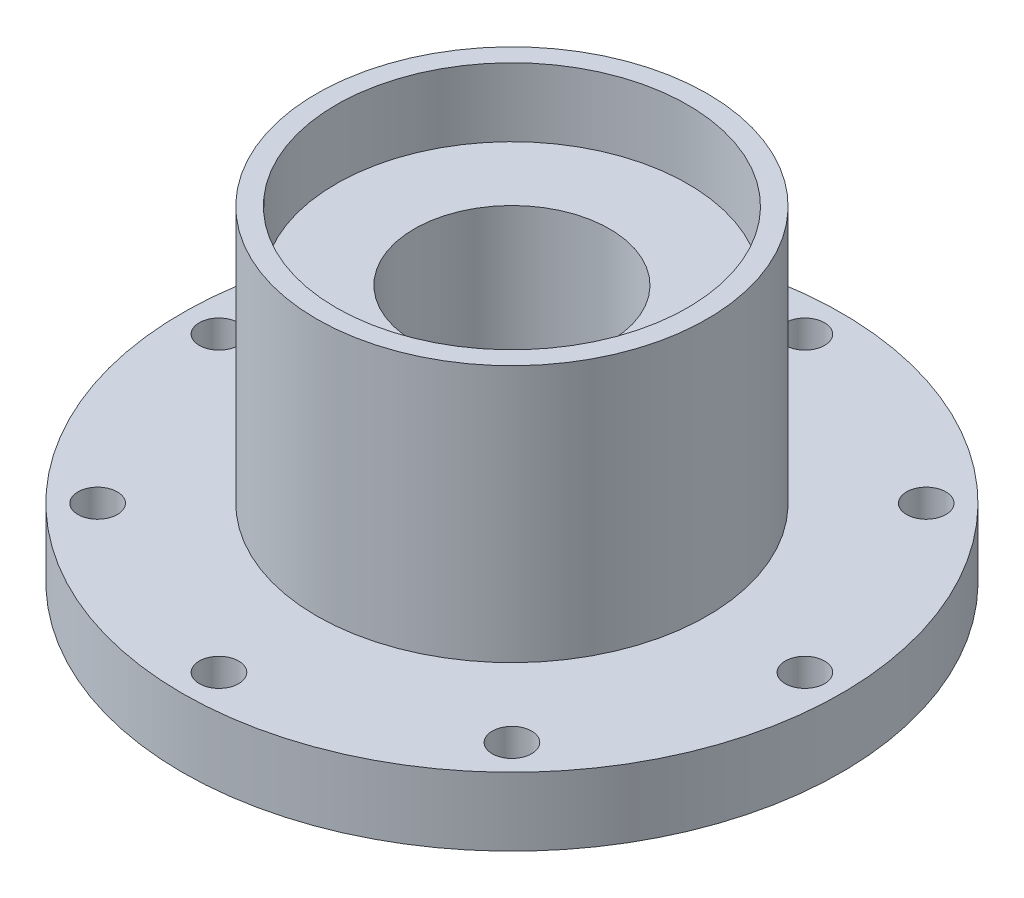
SolidWorks part; units mm, degrees
ref_plane "Front Plane" through (0, 0, 0) normal (0, 0, 1) x (1, 0, 0)
ref_plane "Top Plane" through (0, 0, 0) normal (0, 1, 0) x (1, 0, 0)
ref_plane "Right Plane" through (0, 0, 0) normal (1, 0, 0) x (0, 0, -1)
sketch "Sketch1" plane through (0, 0, 0) normal (1, 0, 0) x (0, 0, -1)
  line L0 (0, 150) -> (0, -163.75) construction
  line L1 (-60, -15.2609) -> (-60, -94.2609)
  line L2 (-60, -94.2609) -> (-101.25, -94.2609)
  line L3 (-101.25, -94.2609) -> (-101.25, -107.2609)
  line L4 (-101.25, -115.2609) -> (-54, -115.2609)
  line L5 (-54, -115.2609) -> (-54, -94.2609)
  line L6 (-54, -94.2609) -> (-34.1, -94.2609)
  line L7 (-30, -94.1609) -> (-30, -36.2609)
  line L8 (-54, -15.2609) -> (-60, -15.2609)
  line L9 (-34.1, -94.2609) -> (-30, -94.1609)
  line L10 (-54, -15.2609) -> (-54, -36.2609)
  line L11 (-54, -36.2609) -> (-30, -36.2609)
  line L12 (-30, -15.2609) -> (-54, -15.2609) construction
  line L13 (-30, -36.2609) -> (-30, -15.2609) construction
  line L17 (-101.25, -107.2609) -> (-101.25, -115.2609) construction
  line L18 (-101.25, -115.2609) -> (-101.25, -107.2609)
  point P10 (-30, -94.2609)
  dimension "D1" = 108
  dimension "D2" = 21
  dimension "D3" = 79
  dimension "D4" = 202.5
  dimension "D5" = 30
  dimension "D6" = 60
  dimension "D7" = 21
  dimension "D8" = 21
revolve "Revolve1" add sketch "Sketch1" angle 360 about L0
sketch "Sketch2" plane through (0, -94.2609, 0) normal (0, 1, 0) x (1, 0, 0)
  circle A0 centre (0, 90) radius 6.05
  circle A1 centre (63.6396, 63.6396) radius 6.05
  circle A2 centre (90, 0) radius 6.05
  circle A3 centre (63.6396, -63.6396) radius 6.05
  circle A4 centre (0, -90) radius 6.05
  circle A5 centre (-63.6396, -63.6396) radius 6.05
  circle A6 centre (-90, 0) radius 6.05
  circle A7 centre (-63.6396, 63.6396) radius 6.05
  point P19 (0, 0)
  dimension "D1" = 90
  dimension "D2" = 12.1
  dimension "D3" = 8
extrude "Cut-Extrude1" cut sketch "Sketch2" along normal through all both and the other way through all
scale "Scale1" scale about centroid uniform scaling yes scale factor 0.25
